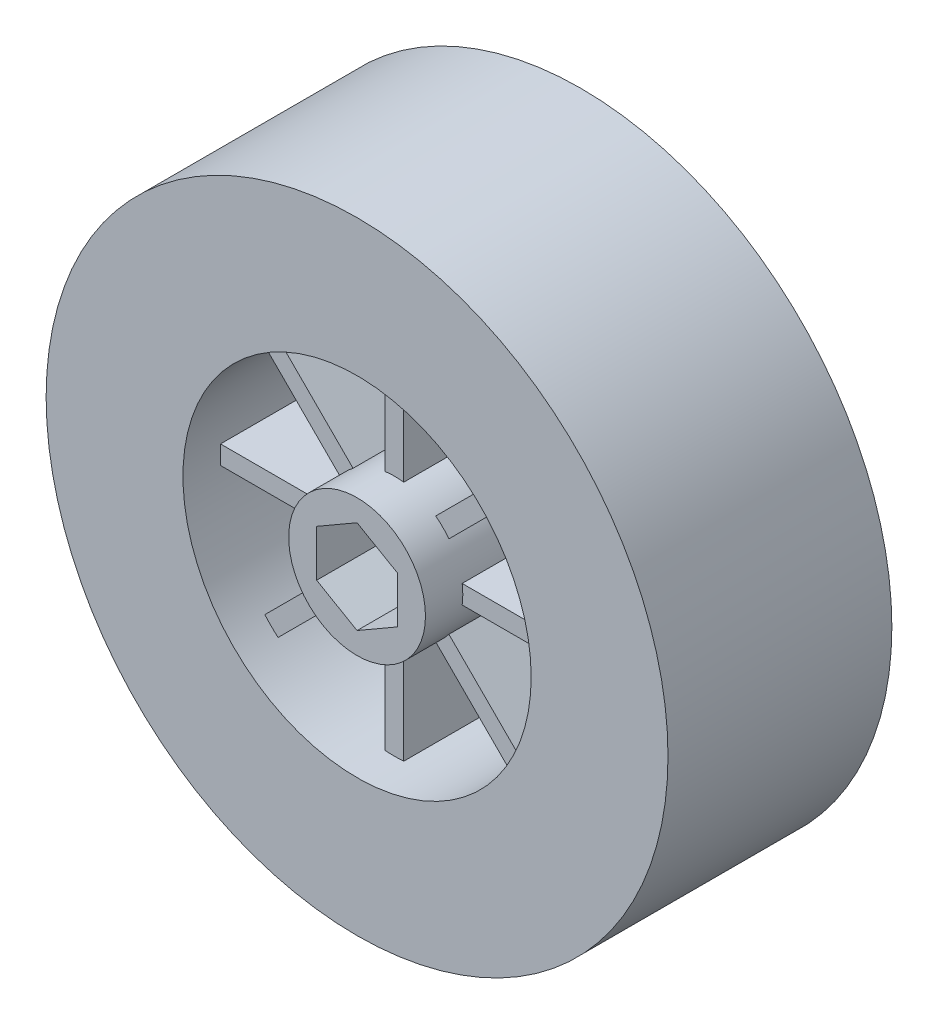
SolidWorks part; units mm, degrees
ref_plane "前视基准面" through (0, 0, 0) normal (0, 0, 1) x (1, 0, 0)
ref_plane "上视基准面" through (0, 0, 0) normal (0, 1, 0) x (1, 0, 0)
ref_plane "右视基准面" through (0, 0, 0) normal (1, 0, 0) x (0, 0, -1)
sketch "草图2" plane through (0, 0, 0) normal (0, 0, 1) x (1, 0, 0)
  circle A0 centre (0, 0) radius 25
  dimension "D1" = 50
extrude "凸台-拉伸1" add sketch "草图2" along normal mid plane 18
sketch "草图3" plane through (0, 0, 9) normal (0, 0, 1) x (1, 0, 0)
  circle A0 centre (0, 0) radius 14
  circle A1 centre (0, 0) radius 5.5
  dimension "D1" = 28
  dimension "D2" = 11
extrude "切除-拉伸1" cut sketch "草图3" against normal blind 3
mirror "镜向1" about plane through (0, 0, 0) normal (0, 0, 1) of "切除-拉伸1"
sketch "草图5" plane through (0, 0, 9) normal (0, 0, 1) x (1, 0, 0)
  line L1 (3.25, -1.8764) -> (3.25, 1.8764)
  line L2 (3.25, 1.8764) -> (0, 3.7528)
  line L3 (0, 3.7528) -> (-3.25, 1.8764)
  line L4 (-3.25, 1.8764) -> (-3.25, -1.8764)
  line L5 (-3.25, -1.8764) -> (0, -3.7528)
  line L6 (0, -3.7528) -> (3.25, -1.8764)
  circle A0 centre (0, 0) radius 3.25 construction
  dimension "D1" = 6.5
extrude "切除-拉伸3" cut sketch "草图5" against normal blind 13
sketch "草图6" plane through (0, 0, -9) normal (0, 0, -1) x (-1, 0, 0)
  circle A0 centre (0, 0) radius 2
  dimension "D1" = 4
extrude "切除-拉伸4" cut sketch "草图6" against normal blind 5
sketch "草图7" plane through (0, 0, -6) normal (0, 0, -1) x (-1, 0, 0)
  line L1 (0.7502, 5.4202) -> (0.7502, 13.9799)
  line L2 (-0.7502, 5.4202) -> (-0.7502, 13.9799)
  line L3 (3.3022, 4.3631) -> (9.3548, 10.4157)
  line L4 (4.3631, 3.3022) -> (10.4157, 9.3548)
  line L5 (5.4202, 0.7502) -> (13.9799, 0.7502)
  line L6 (5.4202, -0.7502) -> (13.9799, -0.7502)
  line L7 (4.3631, -3.3022) -> (10.4157, -9.3548)
  line L8 (3.3022, -4.3631) -> (9.3548, -10.4157)
  line L9 (0.7502, -5.4202) -> (0.7502, -13.9799)
  line L10 (-0.7502, -5.4202) -> (-0.7502, -13.9799)
  line L11 (-3.3022, -4.3631) -> (-9.3548, -10.4157)
  line L12 (-4.3631, -3.3022) -> (-10.4157, -9.3548)
  line L13 (-5.4202, -0.7502) -> (-13.9799, -0.7502)
  line L14 (-5.4202, 0.7502) -> (-13.9799, 0.7502)
  line L15 (-4.3631, 3.3022) -> (-10.4157, 9.3548)
  line L16 (-3.3022, 4.3631) -> (-9.3548, 10.4157)
  circle A1 centre (0, 0) radius 5.5 construction
  circle A4 centre (0, 0) radius 14 construction
  circle A5 centre (0, 0) radius 5.5
  circle A6 centre (0, 0) radius 14
  point P44 (0, 0)
  circle M23 centre (0, 0) radius 14
  circle M24 centre (0, 0) radius 5.5
  dimension "D2" = 8
extrude "切除-拉伸5" cut sketch "草图7" against normal blind 20 contours L3 L1 M24 M23
pattern_circular "阵列(圆周)1" count 8 over 360 about axis through (0, 0, 0) along (0, 0, 1) of "切除-拉伸5"
sketch "草图8" plane through (0, 0, -9) normal (0, 0, -1) x (-1, 0, 0)
  circle A0 centre (0, 0) radius 5.5 construction
  circle A1 centre (0, 0) radius 5.5
extrude "切除-拉伸6" cut sketch "草图8" against normal blind 3
